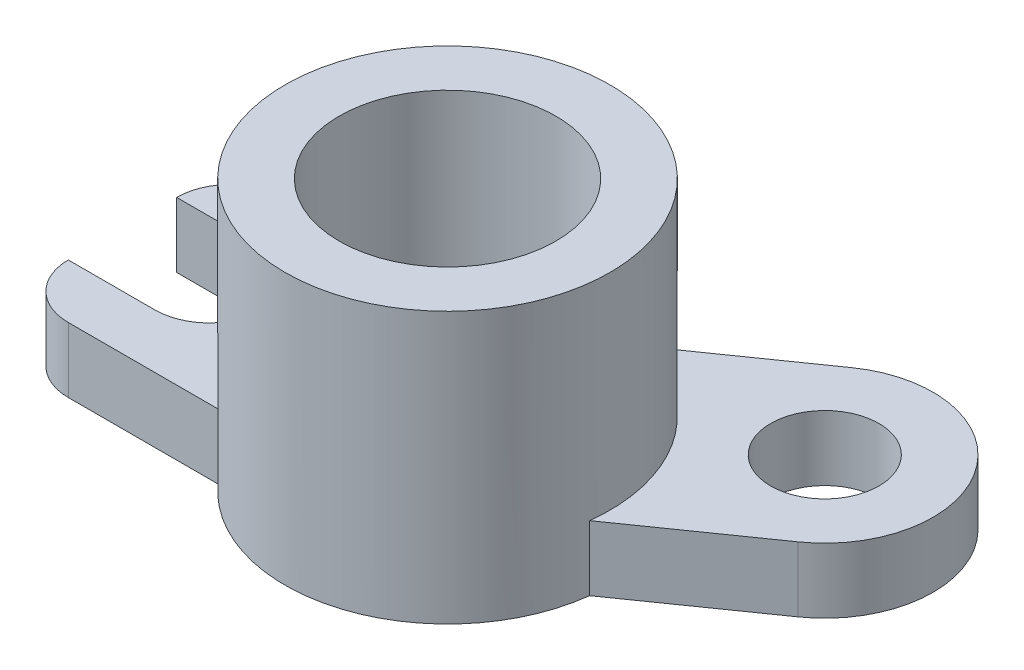
SolidWorks part; units mm, degrees
ref_plane "前基準面" through (0, 0, 0) normal (0, 0, 1) x (1, 0, 0)
ref_plane "上基準面" through (0, 0, 0) normal (0, 1, 0) x (1, 0, 0)
ref_plane "右基準面" through (0, 0, 0) normal (1, 0, 0) x (0, 0, -1)
sketch "草圖1" plane through (0, 0, 0) normal (0, 1, 0) x (1, 0, 0)
  circle A0 centre (0, 0) radius 10
  circle A1 centre (0, 0) radius 15
  dimension "D1" = 20
  dimension "D2" = 30
extrude "伸長1" add sketch "草圖1" along normal blind 25
sketch "草圖2" plane through (0, 0, 0) normal (0, 1, 0) x (1, 0, 0)
  line L0 (0, 0) -> (23.8613, 16.7078) construction
  line L1 (0, 0) -> (-33.6442, 0) construction
  line L2 (-11.1803, 10) -> (-25, 10)
  line L3 (-30, 5) -> (-30, -5)
  line L4 (3.4226, 14.6043) -> (14.743, 22.5309)
  line L5 (26.2146, 6.1479) -> (14.8942, -1.7787)
  line L6 (-11.1803, -10) -> (-25, -10)
  line L7 (-30, 5) -> (-22, 5)
  line L8 (-22, -5) -> (-30, -5)
  circle A0 centre (0, 0) radius 15 construction
  circle A1 centre (0, 0) radius 15
  arc A2 (-25, 10) -> (-30, 5) centre (-25, 5) ccw
  arc A3 (14.743, 22.5309) -> (26.2146, 6.1479) centre (20.4788, 14.3394) cw
  circle A4 centre (20.4788, 14.3394) radius 5
  arc A5 (-25, -10) -> (-30, -5) centre (-25, -5) cw
  arc A6 (-22, 5) -> (-22, -5) centre (-22, 0) cw
  point P19 (-30, 0)
  dimension "D1" = 5
  dimension "D4" = 10
  dimension "D5" = 10
  dimension "D2" = 35
  dimension "D3" = 25
  dimension "D6" = 20
  dimension "D7" = 8
  dimension "D8" = 30
extrude "伸長2" add sketch "草圖2" along normal blind 6 contours L7 A6 L8 A5 L6 A1 L2 A2 | A3 L4 A1 L5 A4
